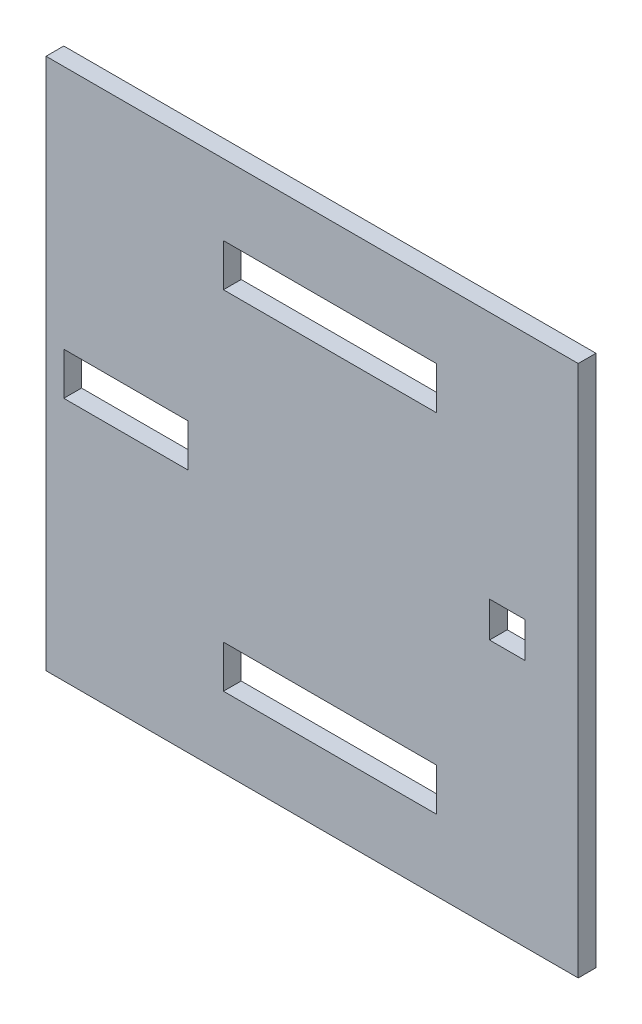
SolidWorks part; units mm, degrees
ref_plane "Plan de face" through (0, 0, 0) normal (0, 0, 1) x (1, 0, 0)
ref_plane "Plan de dessus" through (0, 0, 0) normal (0, 1, 0) x (1, 0, 0)
ref_plane "Plan de droite" through (0, 0, 0) normal (1, 0, 0) x (0, 0, -1)
sketch "Esquisse2" plane through (0, 0, 0) normal (0, 0, 1) x (1, 0, 0)
  line L1 (-75, -75) -> (75, -75)
  line L2 (-75, -75) -> (-75, 75)
  line L3 (-75, 75) -> (75, 75)
  line L4 (75, -75) -> (75, 75)
  point P0 (0, 0)
  dimension "D1" = 150
  dimension "D2" = 150
extrude "Boss.-Extru.1" add sketch "Esquisse2" along normal blind 5
sketch "Esquisse3" plane through (0, 0, 5) normal (0, 0, 1) x (1, 0, 0)
  line L0 (75, 75) -> (-75, 75) construction
  line L1 (35, 55) -> (-25, 55)
  line L2 (35, 55) -> (35, 43)
  line L3 (35, 43) -> (-25, 43)
  line L4 (-25, 55) -> (-25, 43)
  line L5 (35, -43) -> (-25, -43)
  line L6 (35, -43) -> (35, -55)
  line L7 (35, -55) -> (-25, -55)
  line L8 (-25, -43) -> (-25, -55)
  line L9 (-35, 6) -> (-70, 6)
  line L10 (-35, 6) -> (-35, -6)
  line L11 (-35, -6) -> (-70, -6)
  line L12 (-70, 6) -> (-70, -6)
  line L13 (-75, -75) -> (75, -75) construction
  line L16 (75, -75) -> (75, 75) construction
  line L18 (-75, 75) -> (-75, -75) construction
  dimension "D1" = 20
  dimension "D2" = 20
  dimension "D3" = 60
  dimension "D4" = 12
  dimension "D5" = 12
  dimension "D6" = 60
  dimension "D7" = 40
  dimension "D8" = 40
  dimension "D9" = 35
  dimension "D10" = 12
  dimension "D11" = 69
  dimension "D12" = 40
extrude "Enlèv. mat.-Extru.3" cut sketch "Esquisse3" against normal through all
sketch "Esquisse4" plane through (0, 0, 5) normal (0, 0, 1) x (1, 0, 0)
  line L0 (-25, 43) -> (35, 43) construction
  line L1 (60, 5) -> (50, 5)
  line L2 (60, 5) -> (60, -5)
  line L3 (60, -5) -> (50, -5)
  line L4 (50, 5) -> (50, -5)
  line L8 (75, -75) -> (75, 75) construction
  dimension "D1" = 38
  dimension "D2" = 10
  dimension "D3" = 10
  dimension "D4" = 15
extrude "Enlèv. mat.-Extru.4" cut sketch "Esquisse4" against normal blind 10
